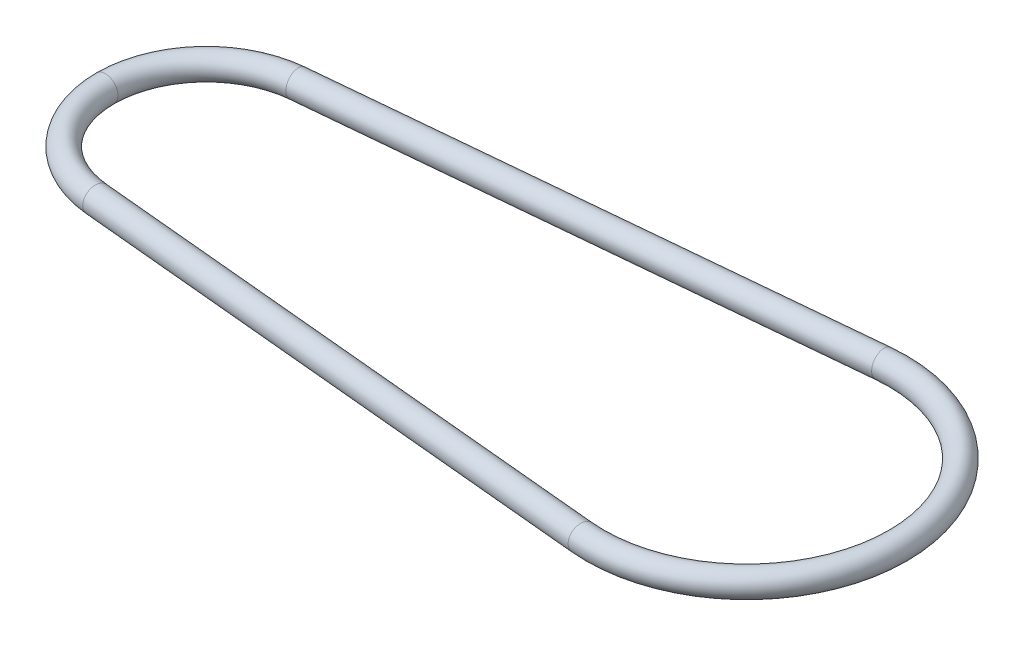
SolidWorks part; units mm, degrees
ref_plane "Front Plane" through (0, 0, 0) normal (0, 0, 1) x (1, 0, 0)
ref_plane "Top Plane" through (0, 0, 0) normal (0, 1, 0) x (1, 0, 0)
ref_plane "Right Plane" through (0, 0, 0) normal (1, 0, 0) x (0, 0, -1)
sketch "Sketch1" plane through (0, 0, 0) normal (0, 1, 0) x (1, 0, 0)
  line L0 (0, 0) -> (136.132, 0) construction
  line L1 (-2.3696, 25.2892) -> (132.5776, 37.9338)
  line L2 (-2.3696, -25.2892) -> (132.5776, -37.9338)
  arc A0 (132.5776, -37.9338) -> (132.5776, 37.9338) centre (136.132, 0) ccw
  arc A1 (-2.3696, 25.2892) -> (-2.3696, -25.2892) centre (0, 0) ccw
  dimension "D2" = 76.2
  dimension "D3" = 50.8
  dimension "D1" = 136.132
sketch "Sketch2" plane through (0, 0, 0) normal (0, 0, 1) x (1, 0, 0)
  line L0 (-2.3696, 0) -> (-25.4, 0) construction
  line L1 (-2.3696, 0) -> (-25.4, 0) construction
  circle A0 centre (-25.4, 0) radius 3.175
  dimension "D1" = 6.35
sweep "Sweep1" add profiles "Sketch2" path "Sketch1"
sketch "Sketch3" plane through (0, 0, 0) normal (0, 0, 1) x (1, 0, 0)
  line L0 (0, 0) -> (0, 27.8082) construction
  line L1 (0, 0) -> (136.13, 0) construction
  line L2 (136.13, 0) -> (136.13, 13.9041) construction
  point P5 (0, 0)
  point P6 (0, 0)
  dimension "D1" = 136.13
